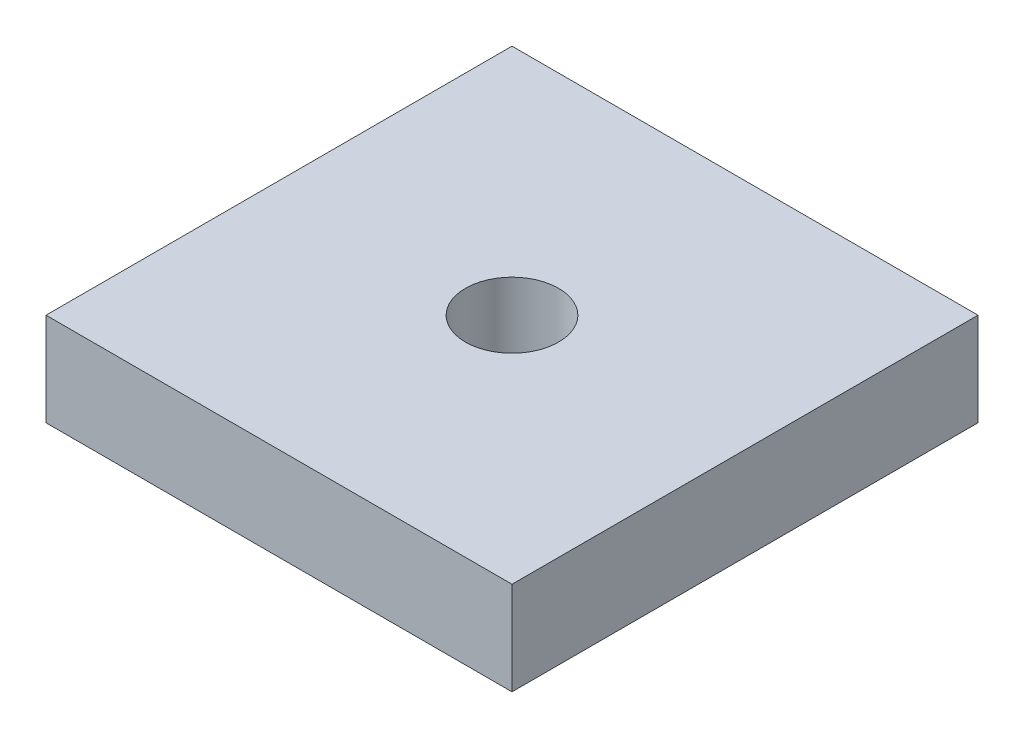
SolidWorks part; units mm, degrees
ref_plane "Спереди" through (0, 0, 0) normal (0, 0, 1) x (1, 0, 0)
ref_plane "Сверху" through (0, 0, 0) normal (0, 1, 0) x (1, 0, 0)
ref_plane "Справа" through (0, 0, 0) normal (1, 0, 0) x (0, 0, -1)
sketch "Эскиз1" plane through (0, 0, 0) normal (0, 1, 0) x (1, 0, 0)
  line L0 (0, 25) -> (0, 0) construction
  line L1 (-25, 25) -> (25, 25)
  line L2 (-25, 25) -> (-25, -25)
  line L3 (-25, -25) -> (25, -25)
  line L4 (25, 25) -> (25, -25)
  line L5 (0, 0) -> (25, 0) construction
  dimension "D1" = 50
  dimension "D2" = 50
extrude "Бобышка-Вытянуть2" add sketch "Эскиз1" along normal blind 10
sketch "Эскиз3" plane through (0, 10, 0) normal (0, 1, 0) x (1, 0, 0)
  circle A0 centre (0, 0) radius 5
  dimension "D1" = 10
extrude "Вырез-Вытянуть2" cut sketch "Эскиз3" against normal through all
